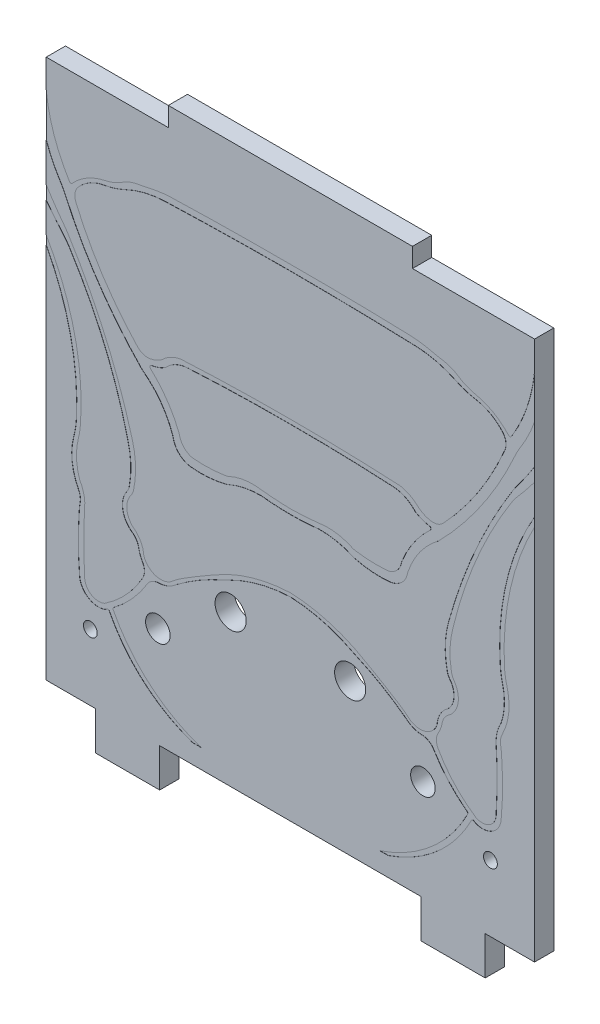
SolidWorks part; units mm, degrees
material "Acrylic (Medium-high impact)"
ref_plane "Front Plane" through (0, 0, 0) normal (0, 0, 1) x (1, 0, 0)
ref_plane "Top Plane" through (0, 0, 0) normal (0, 1, 0) x (1, 0, 0)
ref_plane "Right Plane" through (0, 0, 0) normal (1, 0, 0) x (0, 0, -1)
sketch "스케치1" plane through (0, 0, 0) normal (0, 0, 1) x (1, 0, 0)
  line L1 (38.1, -42.1) -> (-38.1, -42.1)
  line L2 (38.1, -42.1) -> (38.1, 42.1)
  line L3 (38.1, 42.1) -> (-38.1, 42.1)
  line L4 (-38.1, -42.1) -> (-38.1, 42.1)
  line L5 (38.1, -42.1) -> (-38.1, 42.1) construction
  line L6 (38.1, 42.1) -> (-38.1, -42.1) construction
  point P0 (0, 0)
  dimension "D1" = 84.2
  dimension "D2" = 76.2
extrude "보스-돌출1" add sketch "스케치1" along normal blind 3
sketch "스케치2" plane through (0, 0, 3) normal (0, 0, 1) x (1, 0, 0)
  line L0 (-2.0683, 69.821) -> (141.9317, 69.821) construction
  line L1 (0, 0) -> (0, 40.3141) construction
  line L2 (0, 0) -> (0, -48.7195) construction
  line L3 (13.9342, -39.1211) -> (15.2635, -39.1211)
  line L4 (-13.9342, -39.1211) -> (-15.2635, -39.1211)
  line L5 (-41.9926, 23.5558) -> (-39.7279, 19.4837)
  line L6 (-41.0418, 27.2099) -> (-41.9926, 32.3251)
  line L7 (39.1781, 35.9061) -> (38.2388, 40.0156)
  line L8 (41.9926, 32.3251) -> (41.0418, 27.2099)
  line L9 (41.9926, 23.5558) -> (39.7279, 19.4837)
  line L10 (-38.2388, 40.0156) -> (-39.1781, 35.9061)
  circle A0 centre (9.3278, -18.4966) radius 2.4282
  circle A1 centre (20.6797, -26.4193) radius 1.917
  circle A2 centre (31.2158, -31.7681) radius 1.0771
  arc A3 (15.6142, 11.1254) -> (15.9291, 11.1119) centre (16.3159, 23.806) ccw
  arc A4 (34.7007, 19.9188) -> (35.331, 20.8316) centre (45.4568, 13.1663) cw
  arc A5 (34.4446, 18.112) -> (35.6004, 19.6596) centre (45.1684, 11.3083) cw
  arc A6 (32.1061, -25.1808) -> (32.1297, -24.4466) centre (44.806, -25.2209) cw
  arc A7 (9.7702, -13.644) -> (10.3595, -13.9414) centre (4.3445, -25.1267) cw
  arc A8 (10.4916, -14.7626) -> (9.7665, -14.4151) centre (15.6152, -3.142) cw
  arc A9 (18.141, -19.3065) -> (17.7877, -19.0317) centre (10.1673, -29.1913) ccw
  arc A10 (16.9144, -17.7722) -> (18.4124, -18.8825) centre (10.1214, -28.5028) cw
  arc A11 (32.9508, -16.5544) -> (32.8173, -15.4566) centre (20.2888, -17.5367) ccw
  arc A12 (33.8049, -7.0179) -> (33.3921, -4.3564) centre (46.0777, -3.7518) cw
  arc A13 (33.0971, -6.982) -> (32.7551, -4.8268) centre (45.4228, -3.9217) cw
  arc A14 (0, -11.239) -> (9.7702, -13.644) centre (-1.0452, -36.5331) cw
  arc A15 (10.3595, -13.9414) -> (16.9144, -17.7722) centre (-40.3222, -108.1871) cw
  arc A16 (18.4124, -18.8825) -> (22.8753, -17.6639) centre (20.2333, -16.7696) ccw
  arc A17 (22.8753, -17.6639) -> (24.6163, -14.5968) centre (26.8194, -17.875) cw
  arc A18 (24.6163, -14.5968) -> (24.8795, -10.5126) centre (22.4134, -12.4043) ccw
  arc A19 (24.4838, -9.662) -> (24.6594, -2.9055) centre (38.2388, -6.6389) cw
  arc A20 (24.6594, -2.9055) -> (34.7007, 19.9188) centre (107.2092, -25.6014) cw
  arc A21 (35.331, 20.8316) -> (41.9926, 32.3251) centre (-7.944, 53.5912) ccw
  arc A22 (23.0576, -20.7793) -> (28.9672, -27.149) centre (39.1781, -11.7493) ccw
  arc A23 (28.9672, -27.149) -> (32.1061, -25.1808) centre (29.9153, -25.1739) ccw
  arc A24 (32.1297, -24.4466) -> (32.0932, -15.7448) centre (-34.529, -20.375) ccw
  arc A25 (32.0932, -15.7448) -> (32.8817, -12.4043) centre (37.8643, -15.3438) cw
  arc A26 (32.8817, -12.4043) -> (33.0971, -6.982) centre (23.6686, -9.323) ccw
  arc A27 (32.7551, -4.8268) -> (41.9926, 23.5558) centre (72.2964, -2.0016) cw
  arc A28 (22.3523, -21.2435) -> (27.5819, -27.0224) centre (39.803, -10.7075) ccw
  arc A29 (28.9672, -27.9736) -> (32.8817, -25.6014) centre (29.9644, -25.2032) ccw
  arc A30 (32.8817, -25.6014) -> (32.9508, -16.5544) centre (-20.1358, -20.6731) ccw
  arc A31 (32.8173, -15.4566) -> (33.0756, -13.8022) centre (35.4476, -15.0199) cw
  arc A32 (33.0756, -13.8022) -> (33.8049, -7.0179) centre (24.6211, -9.462) ccw
  arc A33 (33.3921, -4.3564) -> (39.7279, 19.4837) centre (74.1104, -2.4156) cw
  arc A34 (20.5652, -20.2012) -> (18.141, -19.3065) centre (20.6797, -16.1594) cw
  arc A35 (23.0799, -18.6301) -> (23.6686, -17.0828) centre (18.8085, -16.1194) ccw
  arc A36 (23.6686, -17.0828) -> (24.8026, -15.3438) centre (26.1018, -17.4302) cw
  arc A37 (24.8026, -15.3438) -> (25.5214, -10.3157) centre (22.5613, -12.4579) ccw
  arc A38 (25.1508, -9.46) -> (25.3969, -3.1986) centre (38.6216, -6.8539) cw
  arc A39 (25.3969, -3.1986) -> (34.4446, 18.112) centre (94.3623, -19.9027) cw
  arc A40 (35.6004, 19.6596) -> (41.0418, 27.2099) centre (-2.1019, 52.5672) ccw
  arc A41 (10.4916, -14.7626) -> (17.7877, -19.0317) centre (-4.4801, -48.7195) cw
  arc A42 (27.6559, -27.3411) -> (13.9342, -39.1211) centre (6.4656, -16.5398) cw
  arc A43 (28.2624, -27.8535) -> (15.2635, -39.1211) centre (7.9221, -17.5198) cw
  arc A44 (0, 0.105) -> (4.3651, 0.3817) centre (-1.5778, 59.5686) ccw
  arc A45 (4.4867, 0.3974) -> (9.5906, -0.3089) centre (5.8739, -8.3727) cw
  arc A46 (10.1541, -0.4802) -> (15.2778, -0.6473) centre (13.3774, 19.7142) ccw
  arc A47 (15.2778, -0.6473) -> (17.2959, 1.3815) centre (14.7175, 1.9282) ccw
  arc A48 (17.4066, 1.7436) -> (21.8535, 8.1652) centre (33.912, -4.9356) cw
  arc A49 (23.1461, 7.342) -> (18.3624, 0.8126) centre (31.2158, -3.5872) ccw
  arc A50 (18.2875, 0.5343) -> (15.73, -1.9848) centre (15.1547, 1.1571) cw
  arc A51 (15.5672, -2.0082) -> (10.0076, -1.5807) centre (13.9513, 13.341) cw
  arc A52 (9.682, -1.4661) -> (4.5345, -0.4231) centre (4.7595, -12.5357) ccw
  arc A53 (4.3499, -0.4344) -> (0, -0.6794) centre (-0.3749, 44.7159) cw
  arc A54 (0, 11.5246) -> (15.6142, 11.1254) centre (1.0919, -251.3096) cw
  arc A55 (15.9291, 11.1119) -> (19.5051, 9.4206) centre (15.7785, 6.1672) cw
  arc A56 (19.5051, 9.4206) -> (21.7254, 8.6023) centre (22.8755, 15.1437) ccw
  arc A57 (23.1461, 7.342) -> (35.05, 24.7922) centre (-19.8909, 49.4858) ccw
  arc A58 (33.4608, 24.7653) -> (23.8501, 10.084) centre (-12.6707, 44.4779) cw
  arc A59 (21.9002, 9.4386) -> (20.0244, 10.2548) centre (22.6716, 13.775) cw
  arc A60 (20.0244, 10.2548) -> (17.1381, 11.7794) centre (16.1789, 6.4689) ccw
  arc A61 (17.1381, 11.7794) -> (0, 12.2182) centre (0.4724, -304.1743) ccw
  arc A62 (35.9248, 26.4128) -> (39.1781, 35.9061) centre (17.9336, 37.8822) ccw
  arc A63 (33.1037, 27.0314) -> (29.0264, 29.3118) centre (27.8869, 22.4889) ccw
  arc A64 (29.0264, 29.3118) -> (25.8091, 30.3303) centre (31.0028, 41.1454) cw
  arc A65 (25.8091, 30.3303) -> (19.5839, 31.8626) centre (19.0368, 16.2283) ccw
  arc A66 (19.5839, 31.8626) -> (0, 32.2301) centre (-1.5376, -571.7007) ccw
  arc A67 (0, 33.1467) -> (18.5666, 32.8853) centre (1.9237, -489.8409) cw
  arc A68 (18.5666, 32.8853) -> (21.9462, 32.4385) centre (18.0212, 15.7555) cw
  arc A69 (21.9462, 32.4385) -> (23.7576, 32.0795) centre (27.9189, 57.8258) ccw
  arc A70 (23.7576, 32.0795) -> (26.2602, 31.0986) centre (22.7445, 25.812) cw
  arc A71 (26.2602, 31.0986) -> (28.831, 30.0307) centre (30.2759, 37.1372) ccw
  arc A72 (28.831, 30.0307) -> (34.0618, 27.0535) centre (26.9064, 20.5652) cw
  arc A73 (34.4657, 27.09) -> (38.2388, 40.0156) centre (13.2069, 40.3091) ccw
  arc A74 (9.7665, -14.4151) -> (0, -11.8105) centre (-0.9967, -35.1607) ccw
  arc A75 (35.05, 24.7922) -> (35.9248, 26.4128) centre (46.6338, 19.5858) cw
  arc A76 (22.3523, -21.2435) -> (20.5652, -20.2012) centre (20.5041, -22.3594) ccw
  arc A77 (23.0576, -20.7793) -> (23.0799, -18.6301) centre (24.9412, -19.7242) cw
  arc A78 (4.3651, 0.3817) -> (4.4867, 0.3974) centre (4.1494, 2.5299) ccw
  arc A79 (4.5345, -0.4231) -> (4.3499, -0.4344) centre (4.5746, -2.5817) ccw
  arc A80 (15.73, -1.9848) -> (15.5672, -2.0082) centre (15.3412, 0.1389) cw
  arc A81 (10.0076, -1.5807) -> (9.682, -1.4661) centre (10.5593, 0.5066) cw
  arc A82 (18.3624, 0.8126) -> (18.2875, 0.5343) centre (20.4051, 0.1134) ccw
  arc A83 (17.2959, 1.3815) -> (17.4066, 1.7436) centre (19.408, 0.9337) cw
  arc A84 (9.5906, -0.3089) -> (10.1541, -0.4802) centre (10.4944, 1.6518) ccw
  arc A85 (25.5214, -10.3157) -> (25.1508, -9.46) centre (27.2705, -9.0499) cw
  arc A86 (24.8795, -10.5126) -> (24.4838, -9.662) centre (26.5925, -9.1985) cw
  arc A87 (23.8501, 10.084) -> (21.9002, 9.4386) centre (22.2783, 11.5642) cw
  arc A88 (33.4608, 24.7653) -> (33.1037, 27.0314) centre (31.4755, 25.6136) ccw
  arc A89 (21.8535, 8.1652) -> (21.7254, 8.6023) centre (21.6814, 8.3521) ccw
  arc A90 (28.6281, -27.7561) -> (28.9672, -27.9736) centre (39.803, -10.7075) ccw
  arc A91 (34.0618, 27.0535) -> (34.4657, 27.09) centre (34.25, 27.2242) ccw
  arc A92 (27.6559, -27.3411) -> (27.5819, -27.0224) centre (27.4296, -27.2257) ccw
  arc A93 (28.2624, -27.8535) -> (28.6281, -27.7561) centre (28.4889, -27.9685) cw
  arc A94 (-28.2624, -27.8535) -> (-28.6281, -27.7561) centre (-28.4889, -27.9685) ccw
  arc A95 (-27.6559, -27.3411) -> (-27.5819, -27.0224) centre (-27.4296, -27.2257) cw
  arc A96 (-34.0618, 27.0535) -> (-34.4657, 27.09) centre (-34.25, 27.2242) cw
  arc A97 (-28.6281, -27.7561) -> (-28.9672, -27.9736) centre (-39.803, -10.7075) cw
  arc A98 (-21.8535, 8.1652) -> (-21.7254, 8.6023) centre (-21.6814, 8.3521) cw
  arc A99 (-33.4608, 24.7653) -> (-33.1037, 27.0314) centre (-31.4755, 25.6136) cw
  arc A100 (-23.8501, 10.084) -> (-21.9002, 9.4386) centre (-22.2783, 11.5642) ccw
  arc A101 (-24.8795, -10.5126) -> (-24.4838, -9.662) centre (-26.5925, -9.1985) ccw
  arc A102 (-25.5214, -10.3157) -> (-25.1508, -9.46) centre (-27.2705, -9.0499) ccw
  arc A103 (-9.5906, -0.3089) -> (-10.1541, -0.4802) centre (-10.4944, 1.6518) cw
  arc A104 (-17.2959, 1.3815) -> (-17.4066, 1.7436) centre (-19.408, 0.9337) ccw
  arc A105 (-18.3624, 0.8126) -> (-18.2875, 0.5343) centre (-20.4051, 0.1134) cw
  arc A106 (-10.0076, -1.5807) -> (-9.682, -1.4661) centre (-10.5593, 0.5066) ccw
  arc A107 (-15.73, -1.9848) -> (-15.5672, -2.0082) centre (-15.3412, 0.1389) ccw
  arc A108 (-4.5345, -0.4231) -> (-4.3499, -0.4344) centre (-4.5746, -2.5817) cw
  arc A109 (-4.3651, 0.3817) -> (-4.4867, 0.3974) centre (-4.1494, 2.5299) cw
  arc A110 (-23.0576, -20.7793) -> (-23.0799, -18.6301) centre (-24.9412, -19.7242) ccw
  arc A111 (-22.3523, -21.2435) -> (-20.5652, -20.2012) centre (-20.5041, -22.3594) cw
  arc A112 (-35.05, 24.7922) -> (-35.9248, 26.4128) centre (-46.6338, 19.5858) ccw
  arc A113 (-9.7665, -14.4151) -> (0, -11.8105) centre (0.9967, -35.1607) cw
  arc A114 (-34.4657, 27.09) -> (-38.2388, 40.0156) centre (-13.2069, 40.3091) cw
  arc A115 (-28.831, 30.0307) -> (-34.0618, 27.0535) centre (-26.9064, 20.5652) ccw
  arc A116 (-26.2602, 31.0986) -> (-28.831, 30.0307) centre (-30.2759, 37.1372) cw
  arc A117 (-23.7576, 32.0795) -> (-26.2602, 31.0986) centre (-22.7445, 25.812) ccw
  arc A118 (-21.9462, 32.4385) -> (-23.7576, 32.0795) centre (-27.9189, 57.8258) cw
  arc A119 (-18.5666, 32.8853) -> (-21.9462, 32.4385) centre (-18.0212, 15.7555) ccw
  arc A120 (0, 33.1467) -> (-18.5666, 32.8853) centre (-1.9237, -489.8409) ccw
  arc A121 (-19.5839, 31.8626) -> (0, 32.2301) centre (1.5376, -571.7007) cw
  arc A122 (-25.8091, 30.3303) -> (-19.5839, 31.8626) centre (-19.0368, 16.2283) cw
  arc A123 (-29.0264, 29.3118) -> (-25.8091, 30.3303) centre (-31.0028, 41.1454) ccw
  arc A124 (-33.1037, 27.0314) -> (-29.0264, 29.3118) centre (-27.8869, 22.4889) cw
  arc A125 (-35.9248, 26.4128) -> (-39.1781, 35.9061) centre (-17.9336, 37.8822) cw
  arc A126 (-17.1381, 11.7794) -> (0, 12.2182) centre (-0.4724, -304.1743) cw
  arc A127 (-20.0244, 10.2548) -> (-17.1381, 11.7794) centre (-16.1789, 6.4689) cw
  arc A128 (-21.9002, 9.4386) -> (-20.0244, 10.2548) centre (-22.6716, 13.775) ccw
  arc A129 (-33.4608, 24.7653) -> (-23.8501, 10.084) centre (12.6707, 44.4779) ccw
  arc A130 (-23.1461, 7.342) -> (-35.05, 24.7922) centre (19.8909, 49.4858) cw
  arc A131 (-19.5051, 9.4206) -> (-21.7254, 8.6023) centre (-22.8755, 15.1437) cw
  arc A132 (-15.9291, 11.1119) -> (-19.5051, 9.4206) centre (-15.7785, 6.1672) ccw
  arc A133 (0, 11.5246) -> (-15.6142, 11.1254) centre (-1.0919, -251.3096) ccw
  arc A134 (-4.3499, -0.4344) -> (0, -0.6794) centre (0.3749, 44.7159) ccw
  arc A135 (-9.682, -1.4661) -> (-4.5345, -0.4231) centre (-4.7595, -12.5357) cw
  arc A136 (-15.5672, -2.0082) -> (-10.0076, -1.5807) centre (-13.9513, 13.341) ccw
  arc A137 (-18.2875, 0.5343) -> (-15.73, -1.9848) centre (-15.1547, 1.1571) ccw
  arc A138 (-23.1461, 7.342) -> (-18.3624, 0.8126) centre (-31.2158, -3.5872) cw
  arc A139 (-17.4066, 1.7436) -> (-21.8535, 8.1652) centre (-33.912, -4.9356) ccw
  arc A140 (-15.2778, -0.6473) -> (-17.2959, 1.3815) centre (-14.7175, 1.9282) cw
  arc A141 (-10.1541, -0.4802) -> (-15.2778, -0.6473) centre (-13.3774, 19.7142) cw
  arc A142 (-4.4867, 0.3974) -> (-9.5906, -0.3089) centre (-5.8739, -8.3727) ccw
  arc A143 (0, 0.105) -> (-4.3651, 0.3817) centre (1.5778, 59.5686) cw
  arc A144 (-28.2624, -27.8535) -> (-15.2635, -39.1211) centre (-7.9221, -17.5198) ccw
  arc A145 (-27.6559, -27.3411) -> (-13.9342, -39.1211) centre (-6.4656, -16.5398) ccw
  arc A146 (-10.4916, -14.7626) -> (-17.7877, -19.0317) centre (4.4801, -48.7195) ccw
  arc A147 (-35.6004, 19.6596) -> (-41.0418, 27.2099) centre (2.1019, 52.5672) cw
  arc A148 (-25.3969, -3.1986) -> (-34.4446, 18.112) centre (-94.3623, -19.9027) ccw
  arc A149 (-25.1508, -9.46) -> (-25.3969, -3.1986) centre (-38.6216, -6.8539) ccw
  arc A150 (-24.8026, -15.3438) -> (-25.5214, -10.3157) centre (-22.5613, -12.4579) cw
  arc A151 (-23.6686, -17.0828) -> (-24.8026, -15.3438) centre (-26.1018, -17.4302) ccw
  arc A152 (-23.0799, -18.6301) -> (-23.6686, -17.0828) centre (-18.8085, -16.1194) cw
  arc A153 (-20.5652, -20.2012) -> (-18.141, -19.3065) centre (-20.6797, -16.1594) ccw
  arc A154 (-33.3921, -4.3564) -> (-39.7279, 19.4837) centre (-74.1104, -2.4156) ccw
  arc A155 (-33.0756, -13.8022) -> (-33.8049, -7.0179) centre (-24.6211, -9.462) cw
  arc A156 (-32.8173, -15.4566) -> (-33.0756, -13.8022) centre (-35.4476, -15.0199) ccw
  arc A157 (-32.8817, -25.6014) -> (-32.9508, -16.5544) centre (20.1358, -20.6731) cw
  arc A158 (-28.9672, -27.9736) -> (-32.8817, -25.6014) centre (-29.9644, -25.2032) cw
  arc A159 (-22.3523, -21.2435) -> (-27.5819, -27.0224) centre (-39.803, -10.7075) cw
  arc A160 (-32.7551, -4.8268) -> (-41.9926, 23.5558) centre (-72.2964, -2.0016) ccw
  arc A161 (-32.8817, -12.4043) -> (-33.0971, -6.982) centre (-23.6686, -9.323) cw
  arc A162 (-32.0932, -15.7448) -> (-32.8817, -12.4043) centre (-37.8643, -15.3438) ccw
  arc A163 (-32.1297, -24.4466) -> (-32.0932, -15.7448) centre (34.529, -20.375) cw
  arc A164 (-28.9672, -27.149) -> (-32.1061, -25.1808) centre (-29.9153, -25.1739) cw
  arc A165 (-23.0576, -20.7793) -> (-28.9672, -27.149) centre (-39.1781, -11.7493) cw
  arc A166 (-35.331, 20.8316) -> (-41.9926, 32.3251) centre (7.944, 53.5912) cw
  arc A167 (-24.6594, -2.9055) -> (-34.7007, 19.9188) centre (-107.2092, -25.6014) ccw
  arc A168 (-24.4838, -9.662) -> (-24.6594, -2.9055) centre (-38.2388, -6.6389) ccw
  arc A169 (-24.6163, -14.5968) -> (-24.8795, -10.5126) centre (-22.4134, -12.4043) cw
  arc A170 (-22.8753, -17.6639) -> (-24.6163, -14.5968) centre (-26.8194, -17.875) ccw
  arc A171 (-18.4124, -18.8825) -> (-22.8753, -17.6639) centre (-20.2333, -16.7696) cw
  arc A172 (-10.3595, -13.9414) -> (-16.9144, -17.7722) centre (40.3222, -108.1871) ccw
  arc A173 (0, -11.239) -> (-9.7702, -13.644) centre (1.0452, -36.5331) ccw
  arc A174 (-33.0971, -6.982) -> (-32.7551, -4.8268) centre (-45.4228, -3.9217) ccw
  arc A175 (-33.8049, -7.0179) -> (-33.3921, -4.3564) centre (-46.0777, -3.7518) ccw
  arc A176 (-32.9508, -16.5544) -> (-32.8173, -15.4566) centre (-20.2888, -17.5367) cw
  arc A177 (-16.9144, -17.7722) -> (-18.4124, -18.8825) centre (-10.1214, -28.5028) ccw
  arc A178 (-18.141, -19.3065) -> (-17.7877, -19.0317) centre (-10.1673, -29.1913) cw
  arc A179 (-10.4916, -14.7626) -> (-9.7665, -14.4151) centre (-15.6152, -3.142) ccw
  arc A180 (-9.7702, -13.644) -> (-10.3595, -13.9414) centre (-4.3445, -25.1267) ccw
  arc A181 (-32.1061, -25.1808) -> (-32.1297, -24.4466) centre (-44.806, -25.2209) ccw
  arc A182 (-34.4446, 18.112) -> (-35.6004, 19.6596) centre (-45.1684, 11.3083) ccw
  arc A183 (-34.7007, 19.9188) -> (-35.331, 20.8316) centre (-45.4568, 13.1663) ccw
  arc A184 (-15.6142, 11.1254) -> (-15.9291, 11.1119) centre (-16.3159, 23.806) cw
  circle A185 centre (-31.2158, -31.7681) radius 1.0771
  circle A186 centre (-20.6797, -26.4193) radius 1.917
  circle A187 centre (-9.3278, -18.4966) radius 2.4282
  point P208 (28.3903, -27.5978)
  point P396 (-28.3903, -27.5978)
  dimension "D1" = 12.7
  dimension "D2" = 2.159
  dimension "D3" = 0.254
  dimension "D4" = 0.254
extrude "컷-돌출2" cut sketch "스케치2" against normal blind 0.025
sketch "스케치4" plane through (0, 0, 0) normal (0, 0, 1) x (1, 0, 0)
  circle A0 centre (31.2158, -31.7681) radius 1.0771 construction
  circle A1 centre (20.6797, -26.4193) radius 1.917 construction
  circle A2 centre (9.3278, -18.4966) radius 2.4282 construction
  circle A3 centre (-31.2158, -31.7681) radius 1.0771 construction
  circle A4 centre (-20.6797, -26.4193) radius 1.917 construction
  circle A5 centre (-9.3278, -18.4966) radius 2.4282 construction
  circle A6 centre (31.2158, -31.7681) radius 1.0771
  circle A7 centre (20.6797, -26.4193) radius 1.917
  circle A8 centre (9.3278, -18.4966) radius 2.4282
  circle A9 centre (-31.2158, -31.7681) radius 1.0771
  circle A10 centre (-20.6797, -26.4193) radius 1.917
  circle A11 centre (-9.3278, -18.4966) radius 2.4282
extrude "컷-돌출7" cut sketch "스케치4" along normal up to surface (3 mm away) up to face at (11.756, -18.4966, 3)
sketch "스케치5" plane through (0, 0, 0) normal (0, 0, -1) x (-1, 0, 0)
  line L0 (0, 42.1) -> (0, -42.1) construction
  line L1 (-38.1, 42.1) -> (38.1, 42.1) construction
  line L2 (38.1, -42.1) -> (-38.1, -42.1) construction
  line L3 (30.4, -42.1) -> (20.4, -42.1)
  line L4 (-30.4, -45.1) -> (-20.4, -45.1)
  line L5 (-30.4, -45.1) -> (-30.4, -42.1)
  line L6 (-30.4, -42.1) -> (-20.4, -42.1)
  line L7 (-20.4, -45.1) -> (-20.4, -42.1)
  line L8 (-30.4, -45.1) -> (-20.4, -42.1) construction
  line L9 (-30.4, -42.1) -> (-20.4, -45.1) construction
  line L10 (20.4, -45.1) -> (20.4, -42.1)
  line L11 (30.4, -45.1) -> (20.4, -45.1)
  line L12 (30.4, -45.1) -> (30.4, -42.1)
  point P6 (-25.4, -43.6)
  dimension "D1" = 25.4
  dimension "D2" = 3
  dimension "D3" = 10
extrude "보스-돌출2" add sketch "스케치5" against normal up to surface (3 mm away) up to face at (0, 32.556, 3)
sketch "스케치7" plane through (0, -45.1, 0) normal (0, -1, 0) x (1, 0, 0)
  line L0 (30.4, 0) -> (30.4, 3) construction
  line L1 (30.4, 3) -> (20.4, 3) construction
  line L2 (20.4, 3) -> (20.4, 0) construction
  line L3 (20.4, 0) -> (30.4, 0) construction
  line L4 (-20.4, 0) -> (-20.4, 3) construction
  line L5 (-20.4, 3) -> (-30.4, 3) construction
  line L6 (-30.4, 3) -> (-30.4, 0) construction
  line L7 (-30.4, 0) -> (-20.4, 0) construction
  line L8 (30.4, 0) -> (30.4, 3)
  line L9 (30.4, 3) -> (20.4, 3)
  line L10 (20.4, 3) -> (20.4, 0)
  line L11 (20.4, 0) -> (30.4, 0)
  line L12 (-20.4, 0) -> (-20.4, 3)
  line L13 (-20.4, 3) -> (-30.4, 3)
  line L14 (-30.4, 3) -> (-30.4, 0)
  line L15 (-30.4, 0) -> (-20.4, 0)
extrude "보스-돌출3" add sketch "스케치7" along normal blind 3
sketch "스케치8" plane through (0, 0, 3) normal (0, 0, 1) x (1, 0, 0)
  line L0 (38.1, 42.1) -> (-38.1, 42.1) construction
  line L1 (-19.05, 45.1) -> (19.05, 45.1)
  line L2 (-19.05, 45.1) -> (-19.05, 42.1)
  line L3 (-19.05, 42.1) -> (19.05, 42.1)
  line L4 (19.05, 45.1) -> (19.05, 42.1)
  line L5 (-19.05, 45.1) -> (19.05, 42.1) construction
  line L6 (-19.05, 42.1) -> (19.05, 45.1) construction
  line L7 (0, 43.6) -> (0, -0.6794) construction
  point P0 (0, 43.6)
  dimension "D1" = 38.1
  dimension "D2" = 3
extrude "보스-돌출4" add sketch "스케치8" against normal up to surface (3 mm away) up to face at (32.2929, -31.7681, 0)
